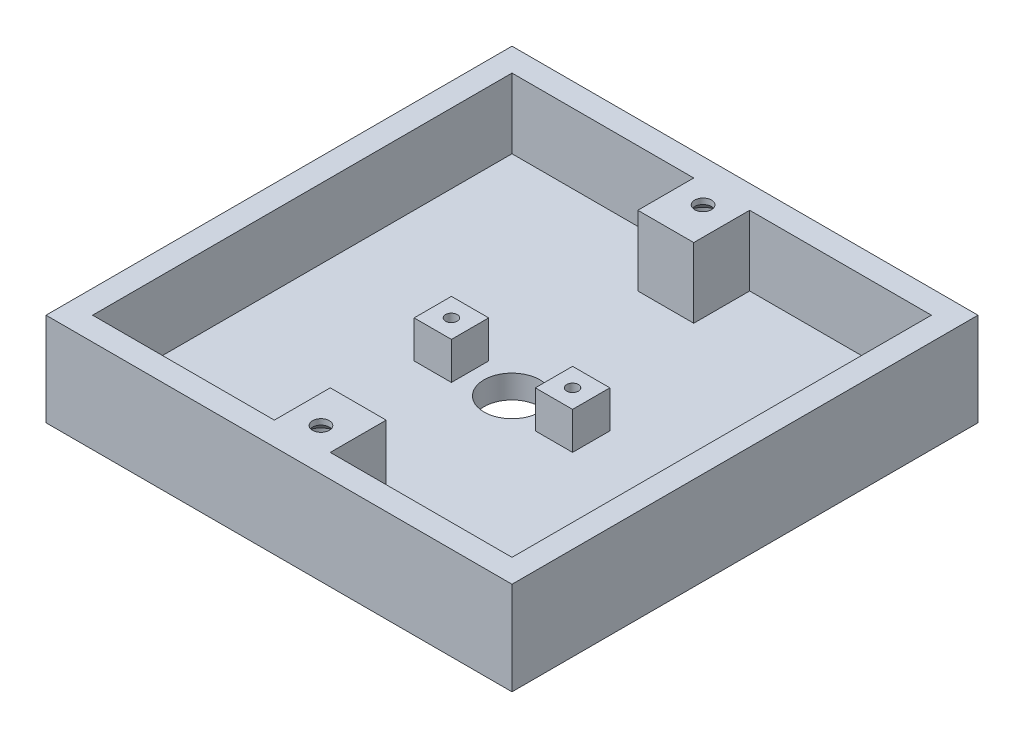
SolidWorks part; units mm, degrees
ref_plane "Front Plane" through (0, 0, 0) normal (0, 0, 1) x (1, 0, 0)
ref_plane "Top Plane" through (0, 0, 0) normal (0, 1, 0) x (1, 0, 0)
ref_plane "Right Plane" through (0, 0, 0) normal (1, 0, 0) x (0, 0, -1)
sketch "Sketch1" plane through (0, 0, 0) normal (0, 1, 0) x (1, 0, 0)
  line L1 (25, 25) -> (-25, 25)
  line L2 (25, 25) -> (25, -25)
  line L3 (25, -25) -> (-25, -25)
  line L4 (-25, 25) -> (-25, -25)
  line L5 (25, 25) -> (-25, -25) construction
  line L6 (25, -25) -> (-25, 25) construction
  point P0 (0, 0)
  dimension "D1" = 50
  dimension "D2" = 50
extrude "Boss-Extrude1" add sketch "Sketch1" along normal blind 10
shell "Shell1" thickness 2.5
sketch "Sketch3" plane through (0, 2.5, 0) normal (0, 1, 0) x (1, 0, 0)
  line L0 (9.676, 17.0496) -> (-10.324, 17.0496) construction
  line L1 (9.676, 17.0496) -> (9.676, -16.9504) construction
  line L2 (-10.3, -16.9504) -> (-10.324, -16.9504) construction
  line L3 (-10.324, 17.0496) -> (-10.324, -16.9504) construction
  line L4 (-10.3, 6.5) -> (-22.5, 6.5)
  line L5 (-22.5, 6.5) -> (-22.5, 22.5)
  line L6 (-22.5, 22.5) -> (0, 22.5)
  line L7 (-10.3, 6.5) -> (-10.3, 13.5)
  line L8 (-10.3, 13.5) -> (0, 13.5)
  line L9 (22.5, 7.28) -> (22.5, 22.5)
  line L10 (10.3, 7.28) -> (22.5, 7.28)
  line L11 (10.3, 7.28) -> (10.3, 13.5)
  line L12 (10.3, 13.5) -> (0, 13.5)
  line L13 (22.5, 22.5) -> (0, 22.5)
  line L14 (10.3, -13.3556) -> (22.5, -13.3556)
  line L15 (5.349, -7.6) -> (5.3465, -14.8199) construction
  line L16 (-22.5, -13.6) -> (-22.5, -22.5)
  line L17 (-10.3, -13.6) -> (-22.5, -13.6)
  line L18 (-10.3, -13.6) -> (-10.3, -20.79)
  line L19 (-10.3, -20.79) -> (0.1901, -20.79)
  line L20 (-22.5, -22.5) -> (-4.4876, -22.5)
  line L21 (-10.324, 17.0496) -> (-10.324, 9.8396) construction
  line L22 (10.3, -13.3556) -> (10.3, -20.79)
  line L23 (9.676, -16.9504) -> (-10.3, -16.9504) construction
  line L24 (10.3, -20.79) -> (0.1901, -20.79)
  line L25 (22.5, -22.5) -> (-4.4876, -22.5)
  line L26 (22.5, -13.3556) -> (22.5, -22.5)
  line L27 (-22.5, -22.5) -> (22.5, -22.5) construction
  line L29 (-22.5, 22.5) -> (-22.5, -22.5) construction
  line L31 (22.5, 22.5) -> (-22.5, 22.5) construction
  point P0 (-4.6776, 2.2035)
  dimension "D1" = 16
extrude "Boss-Extrude2" [suppressed] add sketch "Sketch3" along normal blind 10
sketch "Sketch5" plane through (0, 2.5, 0) normal (0, 1, 0) x (1, 0, 0)
  line L6 (-25, -25) -> (25, -25) construction
  line L7 (-22.5, -22.5) -> (22.5, -22.5) construction
  line L8 (-3, -16.5) -> (3, -16.5)
  line L9 (-3, -16.5) -> (-3, -22.5)
  line L10 (-3, -22.5) -> (3, -22.5)
  line L11 (3, -16.5) -> (3, -22.5)
  line L12 (-3, -16.5) -> (3, -22.5) construction
  line L13 (-3, -22.5) -> (3, -16.5) construction
  point P6 (0, -19.5)
  dimension "D3" = 5.5
extrude "Boss-Extrude3" add sketch "Sketch5" along normal up to surface (7.5 mm away) up to face at (0, 10, 0)
sketch "Sketch6" plane through (0, 10, 0) normal (0, 1, 0) x (1, 0, 0)
  line L0 (3, -22.5) -> (-3, -16.5)
  point P2 (0, 0)
  point P6 (0, -19.5)
hole_wizard "CSK SLOT for M1.6 Countersunk Flat Head Screw1" positions "Sketch7" profile "Sketch8" size "M1.6" standard "ISO" slot yes end condition through all
sketch "Sketch7" plane through (0, 0, 0) normal (0, -1, 0) x (-1, 0, 0)
  line L0 (25, -25) -> (-25, -25) construction
  point P0 (0, -20.5)
  dimension "D1" = 4.5
sketch "Sketch8" plane through (0, 0, 20.5) normal (1, 0, 0) x (0, 0, -1)
  line L0 (0, 0) -> (0, 10)
  line L1 (0, 10) -> (0.9, 10)
  line L2 (0.9, 10) -> (0.9, 9.4)
  line L3 (0.9, 9.4) -> (1.8, 8.5)
  line L4 (1.8, 8.5) -> (1.8, 0)
  line L6 (1.8, 0) -> (0, 0)
  line L7 (-0.9, 9.4) -> (-1.8, 8.5) construction
  line L11 (0, -6.35) -> (0, 107.95) construction
  dimension "Thru Hole Dia." = 1.8
  dimension "Thru Hole Depth" = 10
  dimension "C'Sink Dia." = 3.6
  dimension "C'Sink Angle" = 90
  dimension "Head Clearance" = 8.5
ref_plane "Plane1" through (0, 0, 0) normal (0, 0, 1) x (1, 0, 0)
mirror "Mirror1" about plane through (0, 0, 0) normal (0, 0, 1) of "CSK SLOT for M1.6 Countersunk Flat Head Screw1", "Boss-Extrude3"
sketch "Sketch9" plane through (0, 0, 0) normal (0, -1, 0) x (1, 0, 0)
  circle A0 centre (0, 0) radius 3
  dimension "D1" = 6
extrude "Cut-Extrude1" cut sketch "Sketch9" against normal through all
sketch "Sketch10" [suppressed] plane through (0, 0, 0) normal (0, -1, 0) x (1, 0, 0)
  line L0 (0, -25) -> (0, -6.5)
  line L1 (25, -25) -> (-25, -25) construction
  line L2 (0, 25) -> (0, 6.5)
  line L3 (-25, 25) -> (25, 25) construction
  point P5 (-37.3824, -3.054)
  point P6 (0, -6.5)
  point P12 (0, 6.5)
  dimension "D1" = 18.5
  dimension "D2" = 18.5
sketch "Sketch11" [suppressed] plane through (0, 2.5, 0) normal (0, 1, 0) x (1, 0, 0)
  line L1 (-2, -4.5) -> (2, -4.5)
  line L2 (-2, -4.5) -> (-2, -8.5)
  line L3 (-2, -8.5) -> (2, -8.5)
  line L4 (2, -4.5) -> (2, -8.5)
  line L5 (-2, -4.5) -> (2, -8.5) construction
  line L6 (-2, -8.5) -> (2, -4.5) construction
  line L7 (-2, 8.5) -> (2, 8.5)
  line L8 (-2, 8.5) -> (-2, 4.5)
  line L9 (-2, 4.5) -> (2, 4.5)
  line L10 (2, 8.5) -> (2, 4.5)
  line L11 (-2, 8.5) -> (2, 4.5) construction
  line L12 (-2, 4.5) -> (2, 8.5) construction
  point P0 (0, -6.5)
  point P6 (0, 6.5)
  dimension "D1" = 4
  dimension "D2" = 4
  dimension "D3" = 4
  dimension "D4" = 4
extrude "Boss-Extrude4" [suppressed] add sketch "Sketch11" along normal blind 4 contours L2 L1 L4 L3 | L8 L7 L10 L9
hole_wizard "M1.6 Tapped Hole1" [suppressed] positions "Sketch12" profile "Sketch13" tap size "M1.6" standard "ISO"
sketch "Sketch12" [suppressed] plane through (0, 0, 0) normal (0, -1, 0) x (-1, 0, 0)
  point P0 (0, -6.5)
  point P3 (0, 6.5)
sketch "Sketch13" plane through (0, 0, 6.5) normal (1, 0, 0) x (0, 0, -1)
  line L0 (0, 0) -> (0, 10)
  line L1 (0, 10) -> (0.625, 10)
  line L2 (0.625, 10) -> (0.625, 0)
  line L5 (0.625, 0) -> (0, 0)
  line L11 (0, -6.35) -> (0, 107.95) construction
  dimension "Thru Tap Drill Dia." = 1.25
  dimension "Thru Tap Drill Depth" = 10
cosmetic thread "Hole Thread1" [suppressed] parameters "D2"=1.6
cosmetic thread "Hole Thread2" [suppressed] parameters "D2"=1.6
sketch "Sketch14" plane through (0, 0, 0) normal (0, -1, 0) x (1, 0, 0)
  line L0 (-25, 0) -> (25, 0)
  line L1 (-25, -25) -> (-25, 25) construction
  line L2 (25, 25) -> (25, -25) construction
  point P6 (-6.5, 0)
  point P7 (6.5, 0)
  dimension "D1" = 18.5
  dimension "D2" = 18.5
sketch "Sketch15" plane through (0, 2.5, 0) normal (0, 1, 0) x (1, 0, 0)
  line L1 (-4.5, -2) -> (-8.5, -2)
  line L2 (-4.5, -2) -> (-4.5, 2)
  line L3 (-4.5, 2) -> (-8.5, 2)
  line L4 (-8.5, -2) -> (-8.5, 2)
  line L5 (-4.5, -2) -> (-8.5, 2) construction
  line L6 (-4.5, 2) -> (-8.5, -2) construction
  line L7 (4.5, -2) -> (8.5, -2)
  line L8 (4.5, -2) -> (4.5, 2)
  line L9 (4.5, 2) -> (8.5, 2)
  line L10 (8.5, -2) -> (8.5, 2)
  line L11 (4.5, -2) -> (8.5, 2) construction
  line L12 (4.5, 2) -> (8.5, -2) construction
  point P0 (-6.5, 0)
  point P6 (6.5, 0)
  dimension "D1" = 4
  dimension "D2" = 4
  dimension "D3" = 4
  dimension "D4" = 4
extrude "Boss-Extrude5" add sketch "Sketch15" along normal blind 4
hole_wizard "M1.6 Tapped Hole2" positions "Sketch16" profile "Sketch17" tap size "M1.6" standard "ISO" end condition through all
sketch "Sketch16" plane through (0, 0, 0) normal (0, -1, 0) x (-1, 0, 0)
  point P0 (-6.5, 0)
  point P3 (6.5, 0)
sketch "Sketch17" plane through (6.5, 0, 0) normal (1, 0, 0) x (0, 0, -1)
  line L0 (0, 0) -> (0, 10)
  line L1 (0, 10) -> (0.625, 10)
  line L2 (0.625, 10) -> (0.625, 0)
  line L5 (0.625, 0) -> (0, 0)
  line L11 (0, -6.35) -> (0, 107.95) construction
  dimension "Thru Tap Drill Dia." = 1.25
  dimension "Thru Tap Drill Depth" = 10
cosmetic thread "Hole Thread3" parameters "D2"=1.6
cosmetic thread "Hole Thread4" parameters "D2"=1.6
